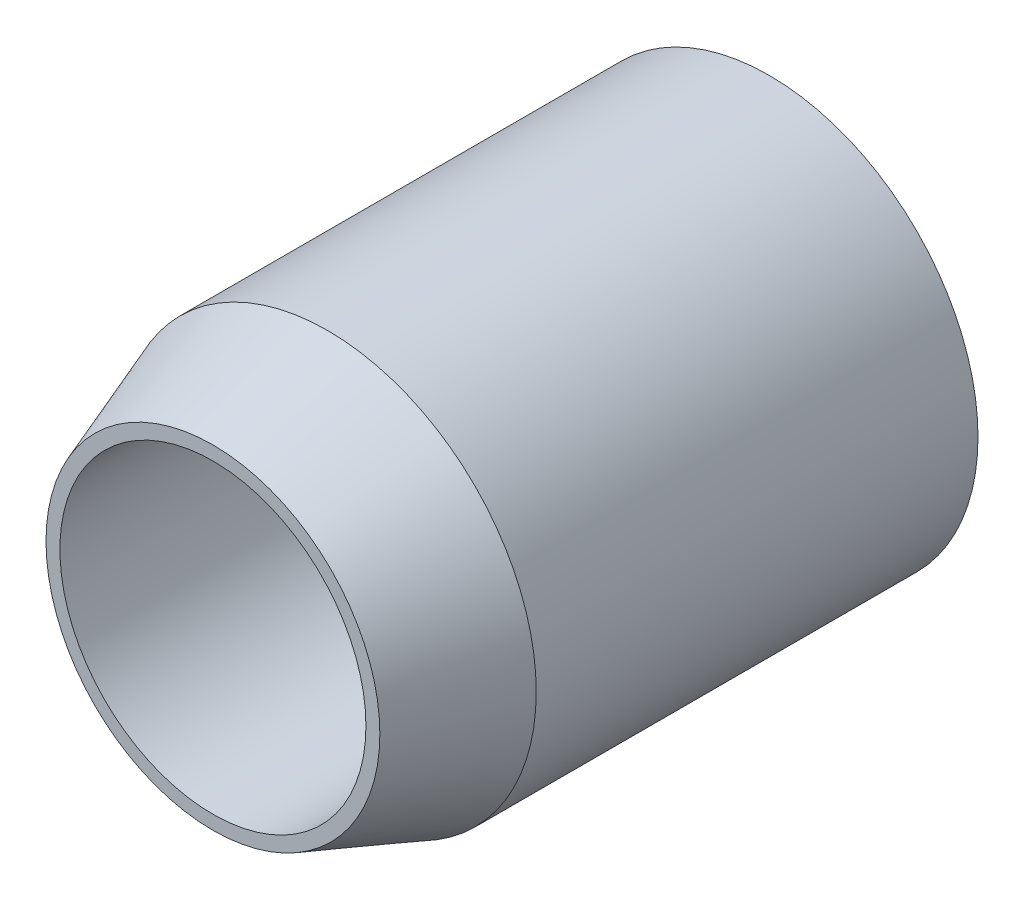
SolidWorks part; units mm, degrees
ref_plane "Front Plane" through (0, 0, 0) normal (0, 0, 1) x (1, 0, 0)
ref_plane "Top Plane" through (0, 0, 0) normal (0, 1, 0) x (1, 0, 0)
ref_plane "Right Plane" through (0, 0, 0) normal (1, 0, 0) x (0, 0, -1)
sketch "Sketch1" plane through (0, 0, 0) normal (0, 0, 1) x (1, 0, 0)
  circle A0 centre (0, 0) radius 7.5
  dimension "D1" = 15
extrude "Boss-Extrude1" add sketch "Sketch1" along normal blind 20
sketch "Sketch2" plane through (0, 0, 20) normal (0, 0, 1) x (1, 0, 0)
  circle A0 centre (0, 0) radius 5.5
  dimension "D1" = 11
extrude "Cut-Extrude1" cut sketch "Sketch2" against normal blind 10
chamfer "Chamfer1" distance 1.5 angle 70 1 edges at (7.5, 0, 20)
sketch "Sketch3" plane through (0, 0, 0) normal (0, 0, -1) x (-1, 0, 0)
  circle A0 centre (0, 0) radius 1.75
  dimension "D1" = 3.5
extrude "Cut-Extrude2" cut sketch "Sketch3" against normal through all
